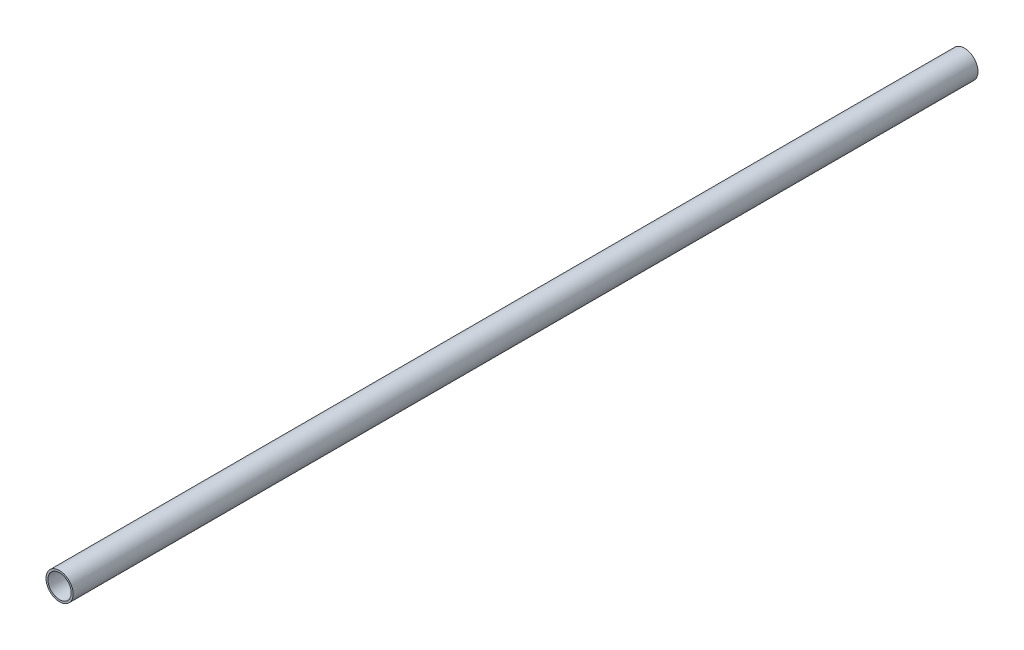
SolidWorks part; units mm, degrees
ref_plane "Alzado" through (0, 0, 0) normal (0, 0, 1) x (1, 0, 0)
ref_plane "Planta" through (0, 0, 0) normal (0, 1, 0) x (1, 0, 0)
ref_plane "Vista lateral" through (0, 0, 0) normal (1, 0, 0) x (0, 0, -1)
sketch "Croquis1" plane through (0, 0, 0) normal (0, 0, 1) x (1, 0, 0)
  circle A0 centre (0, 0) radius 1.8
  circle A1 centre (0, 0) radius 1.55
  dimension "D1" = 3.6
  dimension "D2" = 0.25
extrude "Saliente-Extruir1" add sketch "Croquis1" along normal blind 120
